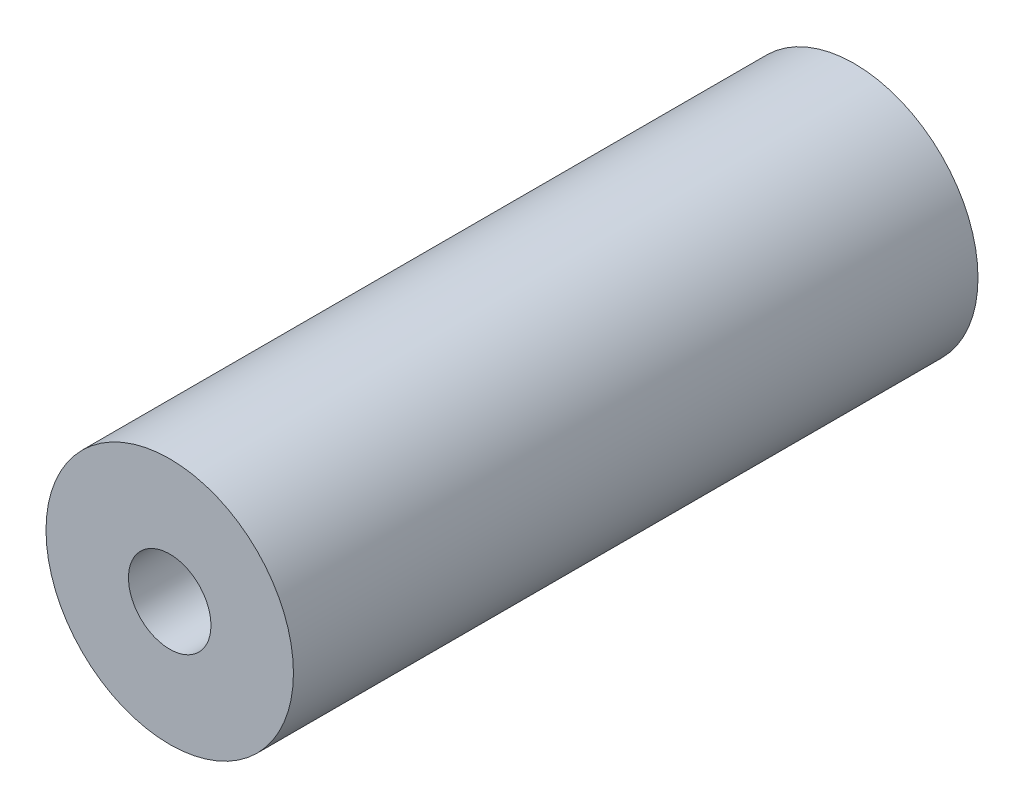
SolidWorks part; units mm, degrees
ref_plane "前视基准面" through (0, 0, 0) normal (0, 0, 1) x (1, 0, 0)
ref_plane "上视基准面" through (0, 0, 0) normal (0, 1, 0) x (1, 0, 0)
ref_plane "右视基准面" through (0, 0, 0) normal (1, 0, 0) x (0, 0, -1)
other "Configuration Table"
sketch "草图1" plane through (0, 0, 0) normal (0, 0, 1) x (1, 0, 0)
  circle A0 centre (0, 0) radius 7.5
  circle A1 centre (0, 0) radius 2.5
  dimension "D1" = 15
  dimension "D2" = 5
extrude "凸台-拉伸1" add sketch "草图1" along normal blind 41.5
sketch "草图2" plane through (0, 0, 41.5) normal (0, 0, 1) x (1, 0, 0)
  circle A0 centre (0, 0) radius 2.5
